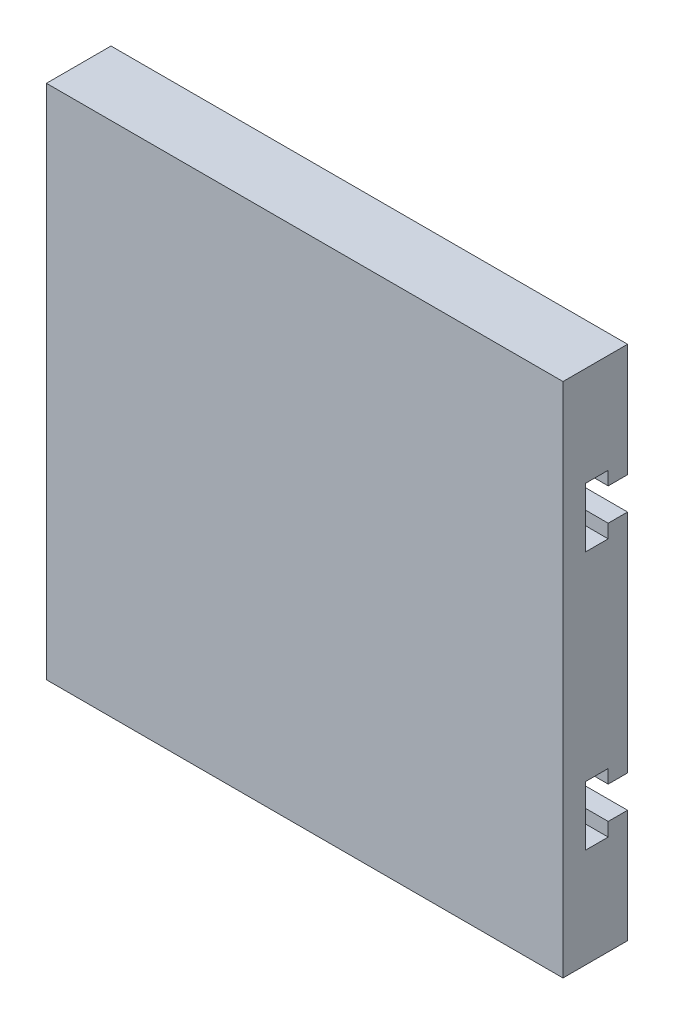
SolidWorks part; units mm, degrees
ref_plane "Plan de face" through (0, 0, 0) normal (0, 0, 1) x (1, 0, 0)
ref_plane "Plan de dessus" through (0, 0, 0) normal (0, 1, 0) x (1, 0, 0)
ref_plane "Plan de droite" through (0, 0, 0) normal (1, 0, 0) x (0, 0, -1)
sketch "Esquisse1" plane through (0, 0, 0) normal (0, 0, 1) x (1, 0, 0)
  line L0 (-37.5, -25) -> (37.5, 25) construction
  line L1 (37.5, 25) -> (37.5, 0) construction
  line L2 (37.5, -25) -> (37.5, 25) construction
  line L3 (37.5, 0) -> (0, 0) construction
  line L5 (-40, -40) -> (40, -40)
  line L6 (-40, -40) -> (-40, 40)
  line L7 (-40, 40) -> (40, 40)
  line L8 (40, -40) -> (40, 40)
  line L9 (-40, -40) -> (40, 40) construction
  line L10 (-40, 40) -> (40, -40) construction
  circle A0 centre (-32.5, 20) radius 2.5 construction
  circle A1 centre (-32.5, -20) radius 2.5 construction
  circle A2 centre (32.5, -20) radius 2.5 construction
  circle A3 centre (32.5, 20) radius 2.5 construction
  circle A4 centre (-32.5, 20) radius 2.5
  circle A5 centre (-32.5, -20) radius 2.5
  circle A6 centre (32.5, -20) radius 2.5
  circle A7 centre (32.5, 20) radius 2.5
  dimension "D1" = 80
  dimension "D2" = 80
extrude "Boss.-Extru.1" add sketch "Esquisse1" along normal blind 10
sketch "Esquisse2" plane through (0, 0, 10) normal (0, 0, 1) x (1, 0, 0)
  line L0 (-40, 0) -> (0, 0) construction
  line L1 (-40, 40) -> (-40, -40) construction
  line L2 (0, 0) -> (0, 40) construction
  line L3 (40, 40) -> (-40, 40) construction
  circle A0 centre (-32.5, 20) radius 4.6
  circle A1 centre (-32.5, -20) radius 4.6
  circle A2 centre (32.5, -20) radius 4.6
  circle A3 centre (32.5, 20) radius 4.6
  dimension "D1" = 9.2
extrude "Enlèv. mat.-Extru.1" cut sketch "Esquisse2" against normal blind 7
ref_plane "Plan1" through (-32.5, 0, 0) normal (-1, 0, 0) x (0, 0, 1)
sketch "Esquisse4" plane through (-40, 0, 0) normal (-1, 0, 0) x (0, 0, 1)
  line L0 (6.5, 24.6) -> (6.5, 15.4)
  line L1 (10, 24.6) -> (3, 24.6) construction
  line L2 (3, 15.4) -> (10, 15.4) construction
  line L3 (6.5, 15.4) -> (3, 15.4)
  line L4 (3, 15.4) -> (3, 24.6) construction
  line L5 (3, 15.4) -> (3, 17.5)
  line L6 (0, 17.5) -> (3, 17.5) construction
  line L7 (3, 17.5) -> (0, 17.5)
  line L8 (0, 22.5) -> (0, 17.5) construction
  line L9 (0, 17.5) -> (0, 22.5)
  line L10 (3, 22.5) -> (0, 22.5) construction
  line L11 (0, 22.5) -> (3, 22.5)
  line L12 (3, 22.5) -> (3, 24.6)
  line L13 (3, 24.6) -> (6.5, 24.6)
extrude "Enlèv. mat.-Extru.2" cut sketch "Esquisse4" against normal blind 7.5
mirror "Symétrie1" about plane through (0, 0, 0) normal (0, 1, 0) of "Enlèv. mat.-Extru.2"
sketch "Esquisse5" plane through (0, 0, 10) normal (0, 0, 1) x (1, 0, 0)
  circle A0 centre (-32.5, 20) radius 4.6
  circle A1 centre (32.5, 20) radius 4.6
  circle A2 centre (32.5, -20) radius 4.6
  circle A3 centre (-32.5, -20) radius 4.6
extrude "Boss.-Extru.2" add sketch "Esquisse5" against normal up to surface (3.5 mm away) up to face at (-37.4, -20, 6.5)
mirror "Symétrie4" about plane through (0, 0, 0) normal (1, 0, 0) of "Symétrie1", "Enlèv. mat.-Extru.2"
